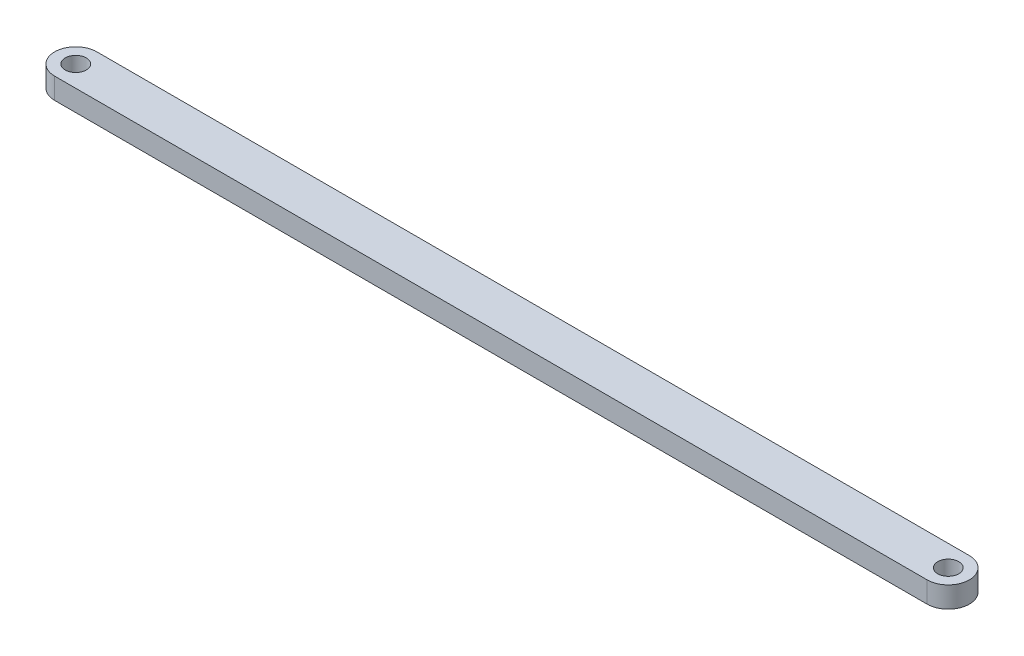
SolidWorks part; units mm, degrees
ref_plane "前视基准面" through (0, 0, 0) normal (0, 0, 1) x (1, 0, 0)
ref_plane "上视基准面" through (0, 0, 0) normal (0, 1, 0) x (1, 0, 0)
ref_plane "右视基准面" through (0, 0, 0) normal (1, 0, 0) x (0, 0, -1)
sketch "草图2" plane through (0, 0, 0) normal (0, 1, 0) x (1, 0, 0)
  line L0 (0, -5) -> (207.06, -5)
  line L1 (0, 5) -> (207.06, 5)
  circle A0 centre (0, 0) radius 5
  circle A1 centre (207.06, 0) radius 5
  circle A2 centre (0, 0) radius 2.5
  circle A3 centre (207.06, 0) radius 2.5
  dimension "D1" = 10
  dimension "D3" = 5
  dimension "D4" = 5
  dimension "D2" = 207.06
extrude "凸台-拉伸1" add sketch "草图2" along normal blind 5 contours A1 L1 A0 L0 | A0 A2 | A1 A3
ref_point "点2"
